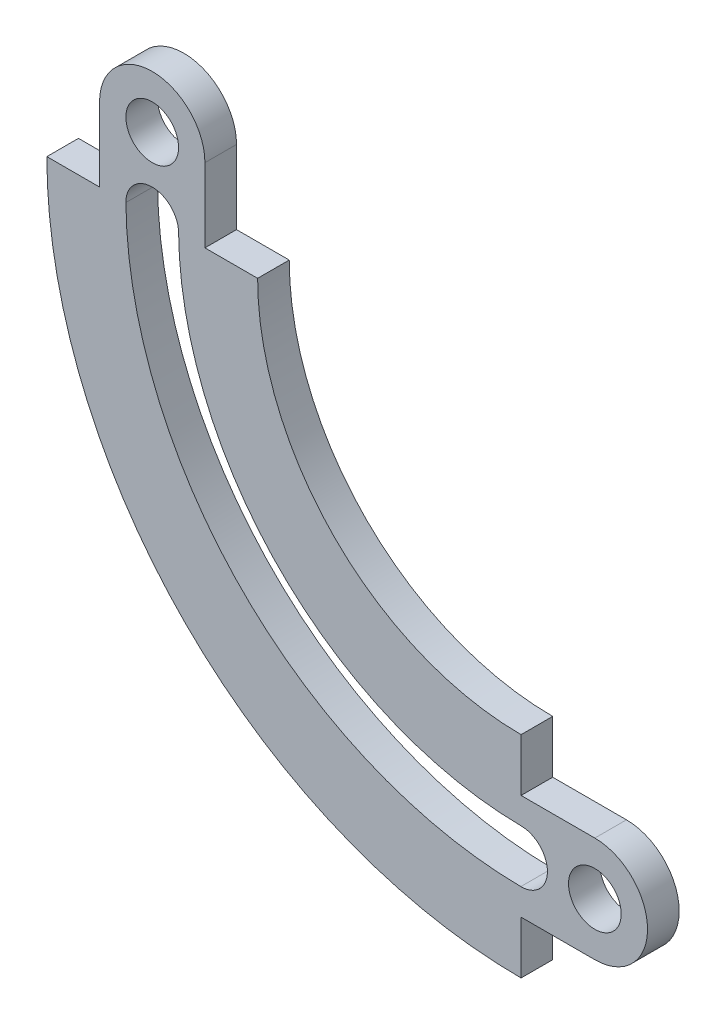
SolidWorks part; units mm, degrees
ref_plane "Alzado" through (0, 0, 0) normal (0, 0, 1) x (1, 0, 0)
ref_plane "Planta" through (0, 0, 0) normal (0, 1, 0) x (1, 0, 0)
ref_plane "Vista lateral" through (0, 0, 0) normal (1, 0, 0) x (0, 0, -1)
sketch "cuadrado" plane through (0, 0, 0) normal (0, 0, 1) x (1, 0, 0)
  line L0 (-90, 81.201) -> (-90, 50081.201) construction
  line L5 (-1098.6765, 90) -> (-80, 90) construction
  line L6 (0, -1038.0947) -> (0, 10) construction
  line L7 (-63.198, 0) -> (49936.802, 0) construction
  line L8 (-50, 90) -> (-60, 90)
  line L9 (0, 40) -> (0, 30)
  line L10 (-80, 90) -> (-90, 90)
  line L12 (-80, 90) -> (-80, 104)
  line L14 (-60, 90) -> (-60, 104)
  line L15 (0, 30) -> (14, 30)
  line L17 (0, 10) -> (14, 10)
  line L20 (-60, 90) -> (49938.6765, 90) construction
  line L23 (0, 30) -> (0, 50085.5619) construction
  line L24 (0, 10) -> (0, 0)
  arc A0 (-50, 90) -> (0, 40) centre (0, 90) ccw
  arc A1 (-90, 90) -> (0, 0) centre (0, 90) ccw
  arc A2 (-80, 104) -> (-60, 104) centre (-70, 104) cw
  arc A3 (14, 30) -> (14, 10) centre (14, 20) cw
  point P4 (0, 0)
  point P24 (0, 0)
  point P27 (24, 20)
  dimension "D3" = 90
  dimension "D6" = 50
  dimension "D1" = 40
  dimension "D2" = 90
  dimension "D4" = 14
  dimension "D5" = 20
  dimension "D7" = 24
  dimension "D8" = 20
extrude "Saliente-Extruir1" add sketch "cuadrado" along normal blind 6
sketch "Croquis3" plane through (0, 0, 0) normal (0, 0, 1) x (1, 0, 0)
  line L0 (-80, 90) -> (-50080, 90) construction
  line L1 (0, 30) -> (0, 50030) construction
  line L2 (0, 0) -> (-50000, 0) construction
  line L3 (-90, 90) -> (-90, -49910) construction
  line L4 (-70, 114) -> (-70, -49886) construction
  line L5 (24, 20) -> (-49976, 20) construction
  line L6 (14, 30) -> (14, -49970) construction
  line L7 (-60, 104) -> (-50060, 104) construction
  arc A0 (-60, 104) -> (-80, 104) centre (-70, 104) ccw construction
  arc A1 (14, 10) -> (14, 30) centre (14, 20) ccw construction
  circle A2 centre (-70, 104) radius 5
  circle A3 centre (14, 20) radius 5
  point P18 (-70, 114)
  point P24 (24, 20)
  dimension "D1" = 10
  dimension "D2" = 10
  dimension "D3" = 10
extrude "Cortar-Extruir1" cut sketch "Croquis3" along normal blind 6
sketch "Croquis4" plane through (0, 0, 0) normal (0, 0, 1) x (1, 0, 0)
  line L0 (-90, 90) -> (49910, 90) construction
  line L2 (0, 30) -> (0, 50030) construction
  line L3 (0, 0) -> (-50000, 0) construction
  line L4 (-90, 90) -> (-90, -49910) construction
  line L5 (-70, 109) -> (-70, -49891) construction
  line L6 (19, 20) -> (-49981, 20) construction
  arc A3 (-69.9998, 90) -> (0, 20.0002) centre (0.6793, 90.6793) ccw construction
  arc A4 (-74.9995, 89.9519) -> (-0.0481, 15.0005) centre (0.6793, 90.6793) ccw
  arc A5 (-65, 90.0481) -> (0.0481, 25) centre (0.6793, 90.6793) ccw
  arc A6 (-65, 90.0481) -> (-74.9995, 89.9519) centre (-69.9998, 90) ccw
  arc A7 (-0.0481, 15.0005) -> (0.0481, 25) centre (0, 20.0002) ccw
  point P20 (-49.3007, 40.6993)
  dimension "D1" = 5
  dimension "D4" = 75.6824
  dimension "D2" = 5
  dimension "D3" = 5
extrude "Cortar-Extruir3" cut sketch "Croquis4" along normal blind 6
